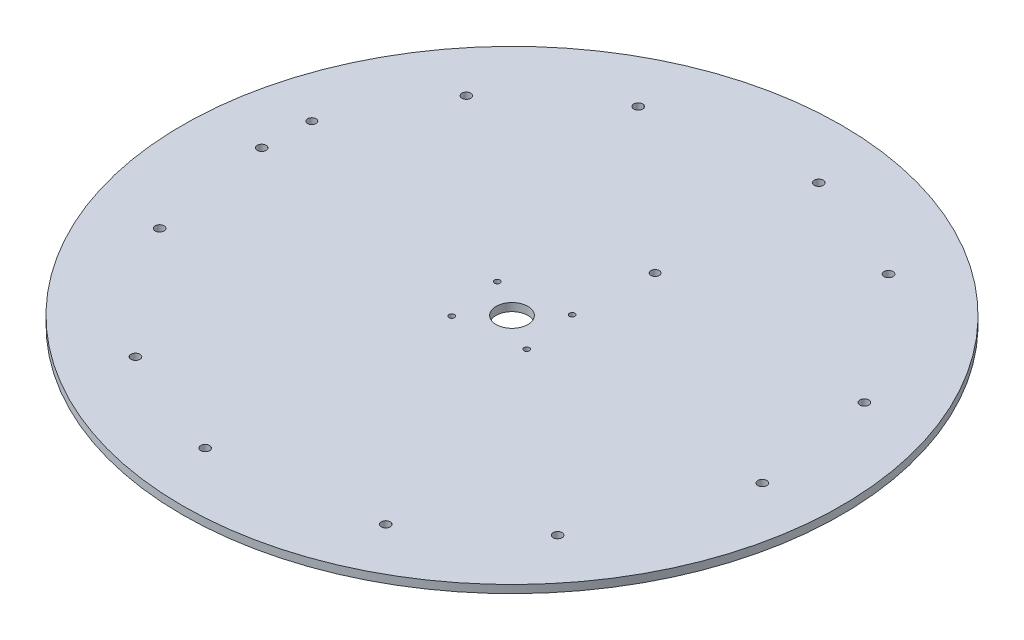
SolidWorks part; units mm, degrees
ref_plane "Front Plane" through (0, 0, 0) normal (0, 0, 1) x (1, 0, 0)
ref_plane "Top Plane" through (0, 0, 0) normal (0, 1, 0) x (1, 0, 0)
ref_plane "Right Plane" through (0, 0, 0) normal (1, 0, 0) x (0, 0, -1)
sketch "Sketch2" plane through (0, 0, 0) normal (0, 1, 0) x (1, 0, 0)
  circle A0 centre (0, 0) radius 125
  dimension "D1" = 250
extrude "Boss-Extrude1" add sketch "Sketch2" along normal blind 3
sketch "Sketch3" plane through (0, 3, 0) normal (0, 1, 0) x (1, 0, 0)
  line L4 (74.6446, 100.2656) -> (65.4599, 76.5843) construction
  line L5 (0, 0) -> (43.5629, 112.3204) construction
  line L6 (74.6446, 100.2656) -> (12.4813, 124.3753) construction
  line L7 (12.4813, 124.3753) -> (3.2966, 100.6941) construction
  line L8 (65.4599, 76.5843) -> (3.2966, 100.6941) construction
  circle A0 centre (0, 0) radius 125 construction
  circle A7 centre (57.8244, 84.9944) radius 1.7
  circle A8 centre (14.6061, 101.7564) radius 1.7
  circle A9 centre (44.6952, -92.5746) radius 1.7
  circle A10 centre (80.8206, -63.5274) radius 1.7
  circle A11 centre (-102.5195, 7.5802) radius 1.7
  circle A12 centre (-95.4267, -38.229) radius 1.7
  point P22 (0, 0)
  point P23 (0.4661, 0.2121)
  dimension "D2" = 3.4
  dimension "D1" = 25.4
  dimension "D3" = 5.08
  dimension "D5" = 66.675
  dimension "D6" = 3
  dimension "D4" = 10.16
extrude "Cut-Extrude1" cut sketch "Sketch3" against normal blind 26 and the other way blind 62
sketch "Sketch4" plane through (0, 3, 0) normal (0, 1, 0) x (1, 0, 0)
  circle A0 centre (0, 0) radius 6
  dimension "D1" = 12
extrude "Cut-Extrude2" cut sketch "Sketch4" against normal blind 12 and the other way blind 55
sketch "Sketch5" plane through (0, 0, 0) normal (0, -1, 0) x (1, 0, 0)
  circle A0 centre (-101.7781, -25.8548) radius 1.6
  circle A1 centre (13.2168, -41.0922) radius 1.6
  dimension "D1" = 3.2
  dimension "D2" = 3.2
extrude "Cut-Extrude3" cut sketch "Sketch5" against normal through all
sketch "Sketch6" plane through (0, 3, 0) normal (0, 1, 0) x (1, 0, 0)
  circle A0 centre (11.1984, 11.6251) radius 1.05
  circle A1 centre (13.8892, -8.3009) radius 1.05
  circle A2 centre (-11.1984, -11.6251) radius 1.05
  circle A3 centre (-13.8892, 8.3009) radius 1.05
extrude "Cut-Extrude4" cut sketch "Sketch6" against normal up to next
pattern_circular "CirPattern1" count 6 over 360 about axis through (0, 0, 0) along (0, 1, 0) of "Cut-Extrude1"
